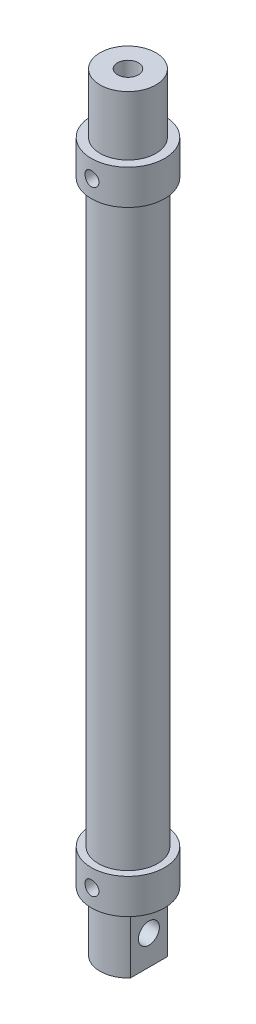
SolidWorks part; units mm, degrees
ref_plane "Front Plane" through (0, 0, 0) normal (0, 0, 1) x (1, 0, 0)
ref_plane "Top Plane" through (0, 0, 0) normal (0, 1, 0) x (1, 0, 0)
ref_plane "Right Plane" through (0, 0, 0) normal (1, 0, 0) x (0, 0, -1)
sketch "Sketch1" plane through (0, 0, 0) normal (0, 1, 0) x (1, 0, 0)
  circle A0 centre (0, 0) radius 8
extrude "Boss-Extrude1" add sketch "Sketch1" along normal blind 17
sketch "Sketch3" plane through (0, 17, 0) normal (0, 1, 0) x (1, 0, 0)
  circle A0 centre (0, 0) radius 10.5
extrude "Boss-Extrude2" add sketch "Sketch3" along normal blind 10 separate body
sketch "Sketch4" plane through (0, 27, 0) normal (0, 1, 0) x (1, 0, 0)
  circle A0 centre (0, 0) radius 8.5
extrude "Boss-Extrude3" add sketch "Sketch4" along normal blind 166 separate body
sketch "Sketch5" plane through (0, 193, 0) normal (0, 1, 0) x (1, 0, 0)
  circle A0 centre (0, 0) radius 10.5
extrude "Boss-Extrude4" add sketch "Sketch5" along normal blind 10 separate body
sketch "Sketch6" plane through (0, 203, 0) normal (0, 1, 0) x (1, 0, 0)
  circle A0 centre (0, 0) radius 8
extrude "Boss-Extrude5" add sketch "Sketch6" along normal blind 17 separate body
sketch "Sketch7" plane through (0, 0, 0) normal (0, -1, 0) x (1, 0, 0)
  line L1 (-6, -5.2915) -> (6, -5.2915)
  line L2 (-6, -5.2915) -> (-6, 5.2915)
  line L3 (-6, 5.2915) -> (6, 5.2915)
  line L4 (6, -5.2915) -> (6, 5.2915)
  line L5 (-6, -5.2915) -> (6, 5.2915) construction
  line L6 (-6, 5.2915) -> (6, -5.2915) construction
  circle A0 centre (0, 0) radius 8 construction
  arc A2 (-6, 5.2915) -> (-6, -5.2915) centre (0, 0) ccw
  arc A3 (6, -5.2915) -> (6, 5.2915) centre (0, 0) ccw
  point P0 (0, 0)
  circle M5 centre (0, 0) radius 8
extrude "Cut-Extrude2" cut sketch "Sketch7" against normal blind 17 contours L2 M5 | L4 M5
sketch "Sketch8" plane through (-6, 0, 0) normal (-1, 0, 0) x (0, 0, 1)
  circle A0 centre (0, 8.5) radius 3
extrude "Cut-Extrude3" cut sketch "Sketch8" against normal through all
sketch "Sketch9" plane through (0, 220, 0) normal (0, 1, 0) x (1, 0, 0)
  circle A0 centre (0, 0) radius 3
extrude "Cut-Extrude4" cut sketch "Sketch9" against normal blind 126
sketch "Sketch10" plane through (0, 0, 0) normal (0, 0, 1) x (1, 0, 0)
  circle A0 centre (0, 198) radius 2
  circle A1 centre (0, 22) radius 2
extrude "Cut-Extrude5" cut sketch "Sketch10" along normal blind 11
